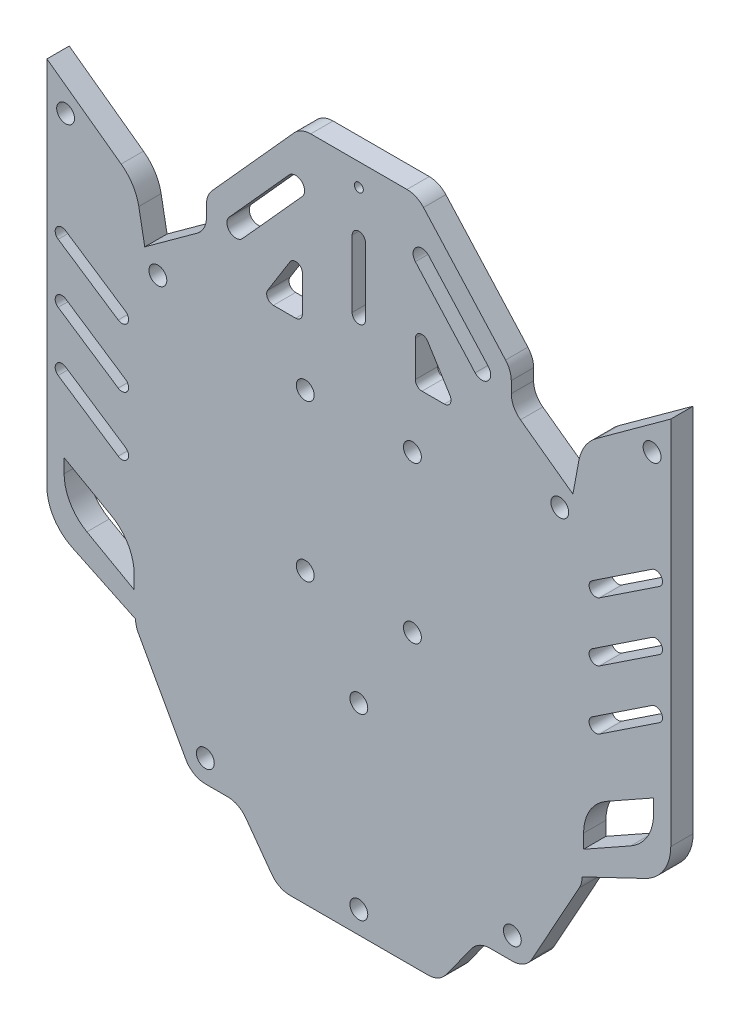
SolidWorks part; units mm, degrees
material "Acrylic (Medium-high impact)"
ref_plane "Front Plane" through (0, 0, 0) normal (0, 0, 1) x (1, 0, 0)
ref_plane "Top Plane" through (0, 0, 0) normal (0, 1, 0) x (1, 0, 0)
ref_plane "Right Plane" through (0, 0, 0) normal (1, 0, 0) x (0, 0, -1)
sketch "Sketch2" plane through (0, 0, 0) normal (0, 0, 1) x (1, 0, 0)
  line L0 (0, 0) -> (0, -150) construction
  line L1 (10.7739, 0) -> (-10.7739, 0)
  line L2 (-14.4896, -1.6543) -> (-32.8523, -22.0482)
  line L3 (-34.1366, -25.3939) -> (-34.1366, -27.9269)
  line L4 (-36.1977, -31.972) -> (-47.9389, -40.5025)
  line L6 (-19.4975, -147.9389) -> (-25.3193, -139.9258)
  line L7 (-29.3644, -137.8647) -> (-34.3726, -137.8647)
  line L8 (-38.7449, -135.2901) -> (-49.3724, -116.1315)
  line L9 (-15.4524, -150) -> (15.4524, -150)
  line L10 (19.4975, -147.9389) -> (25.3193, -139.9258)
  line L11 (29.3644, -137.8647) -> (34.3726, -137.8647)
  line L12 (38.7449, -135.2901) -> (49.3724, -116.1315)
  line L14 (36.1977, -31.972) -> (47.9389, -40.5025)
  line L15 (34.1366, -25.3939) -> (34.1366, -27.9269)
  line L16 (14.4896, -1.6543) -> (32.8523, -22.0482)
  line L17 (-14.147, -11.7352) -> (-27.5296, -26.5981) construction
  line L18 (-12.6607, -13.0735) -> (-26.0433, -27.9364)
  line L19 (-15.6333, -10.397) -> (-29.0159, -25.2599)
  line L20 (14.147, -37.4364) -> (19.147, -37.4364)
  line L21 (-14.147, -37.4364) -> (-19.147, -37.4364)
  line L22 (-12.647, -27.9364) -> (-12.647, -35.9364)
  line L24 (20.419, -35.1414) -> (15.419, -27.1414)
  line L26 (-20.419, -35.1414) -> (-15.419, -27.1414)
  line L27 (12.647, -27.9364) -> (12.647, -35.9364)
  line L28 (14.147, -11.7352) -> (27.5296, -26.5981) construction
  line L29 (12.6607, -13.0735) -> (26.0433, -27.9364)
  line L30 (15.6333, -10.397) -> (29.0159, -25.2599)
  line L31 (0, -15) -> (0, -30) construction
  line L32 (1.5, -15) -> (1.5, -30)
  line L33 (-1.5, -15) -> (-1.5, -30)
  line L34 (0, -50.308) -> (-12, -50.308) construction
  line L35 (14.147, -123.5201) -> (-14.147, -123.5201) construction
  line L36 (-50, -113.7061) -> (-64.1616, -106.9352)
  line L37 (-69.8481, -97.9134) -> (-69.8481, -15)
  line L38 (-69.8481, -15) -> (-53.2247, -27.0776)
  line L39 (-49.2712, -33.3393) -> (-47.9389, -40.5025)
  line L40 (-66.495, -47.4704) -> (-53.0582, -56.398) construction
  line L41 (-65.6648, -46.221) -> (-52.2281, -55.1487)
  line L42 (-67.3251, -48.7198) -> (-53.8883, -57.6474)
  line L43 (-66.495, -60.6771) -> (-53.0582, -69.6047) construction
  line L44 (-65.6648, -59.4277) -> (-52.2281, -68.3553)
  line L45 (-67.3251, -61.9264) -> (-53.8883, -70.8541)
  line L46 (-66.495, -73.8837) -> (-53.0582, -82.8114) construction
  line L47 (-65.6648, -72.6343) -> (-52.2281, -81.562)
  line L48 (-67.3251, -75.1331) -> (-53.8883, -84.0607)
  line L49 (-50.3296, -108.1791) -> (-60.8932, -102.2433)
  line L50 (-65.9945, -93.5254) -> (-65.9945, -90.4053)
  line L51 (-65.9945, -90.4053) -> (-55.4309, -96.3411)
  line L52 (-50.3296, -105.059) -> (-50.3296, -108.1791)
  line L53 (66.495, -47.4704) -> (53.0582, -56.398) construction
  line L54 (65.6648, -46.221) -> (52.2281, -55.1487)
  line L55 (67.3251, -48.7198) -> (53.8883, -57.6474)
  line L56 (66.495, -60.6771) -> (53.0582, -69.6047) construction
  line L57 (65.6648, -59.4277) -> (52.2281, -68.3553)
  line L58 (67.3251, -61.9264) -> (53.8883, -70.8541)
  line L59 (66.495, -73.8837) -> (53.0582, -82.8114) construction
  line L60 (65.6648, -72.6343) -> (52.2281, -81.562)
  line L61 (67.3251, -75.1331) -> (53.8883, -84.0607)
  line L62 (65.9945, -90.4053) -> (55.4309, -96.3411)
  line L63 (65.9945, -93.5254) -> (65.9945, -90.4053)
  line L64 (50.3296, -108.1791) -> (60.8932, -102.2433)
  line L65 (50.3296, -105.059) -> (50.3296, -108.1791)
  line L66 (50, -113.7061) -> (64.1616, -106.9352)
  line L67 (69.8481, -97.9134) -> (69.8481, -15)
  line L68 (69.8481, -15) -> (53.2247, -27.0776)
  line L69 (49.2712, -33.3393) -> (47.9389, -40.5025)
  arc A0 (-50, -113.7061) -> (-49.3724, -116.1315) centre (-45, -113.7061) ccw
  arc A1 (-19.4975, -147.9389) -> (-15.4524, -150) centre (-15.4524, -145) ccw
  arc A2 (-25.3193, -139.9258) -> (-29.3644, -137.8647) centre (-29.3644, -142.8647) ccw
  arc A3 (-34.3726, -137.8647) -> (-38.7449, -135.2901) centre (-34.3726, -132.8647) cw
  arc A5 (-34.1366, -27.9269) -> (-36.1977, -31.972) centre (-39.1366, -27.9269) cw
  arc A6 (-32.8523, -22.0482) -> (-34.1366, -25.3939) centre (-29.1366, -25.3939) ccw
  arc A7 (-10.7739, 0) -> (-14.4896, -1.6543) centre (-10.7739, -5) ccw
  arc A8 (19.4975, -147.9389) -> (15.4524, -150) centre (15.4524, -145) cw
  arc A9 (25.3193, -139.9258) -> (29.3644, -137.8647) centre (29.3644, -142.8647) cw
  arc A10 (34.3726, -137.8647) -> (38.7449, -135.2901) centre (34.3726, -132.8647) ccw
  arc A11 (50, -113.7061) -> (49.3724, -116.1315) centre (45, -113.7061) cw
  arc A13 (34.1366, -27.9269) -> (36.1977, -31.972) centre (39.1366, -27.9269) ccw
  arc A14 (32.8523, -22.0482) -> (34.1366, -25.3939) centre (29.1366, -25.3939) cw
  arc A15 (10.7739, 0) -> (14.4896, -1.6543) centre (10.7739, -5) cw
  arc A16 (-12.6607, -13.0735) -> (-15.6333, -10.397) centre (-14.147, -11.7352) ccw
  arc A17 (-29.0159, -25.2599) -> (-26.0433, -27.9364) centre (-27.5296, -26.5981) ccw
  circle A18 centre (0, -5) radius 1
  arc A19 (-12.647, -27.9364) -> (-15.419, -27.1414) centre (-14.147, -27.9364) ccw
  arc A20 (-14.147, -37.4364) -> (-12.647, -35.9364) centre (-14.147, -35.9364) ccw
  arc A21 (-14.147, -37.4364) -> (-12.647, -35.9364) centre (-14.147, -35.9364) ccw
  arc A22 (-20.419, -35.1414) -> (-19.147, -37.4364) centre (-19.147, -35.9364) ccw
  arc A23 (20.419, -35.1414) -> (19.147, -37.4364) centre (19.147, -35.9364) cw
  arc A24 (12.647, -27.9364) -> (15.419, -27.1414) centre (14.147, -27.9364) cw
  arc A25 (14.147, -37.4364) -> (12.647, -35.9364) centre (14.147, -35.9364) cw
  arc A26 (12.6607, -13.0735) -> (15.6333, -10.397) centre (14.147, -11.7352) cw
  arc A27 (29.0159, -25.2599) -> (26.0433, -27.9364) centre (27.5296, -26.5981) cw
  arc A28 (1.5, -15) -> (-1.5, -15) centre (0, -15) ccw
  arc A29 (-1.5, -30) -> (1.5, -30) centre (0, -30) ccw
  circle A30 centre (0, -145) radius 2
  circle A31 centre (0, -105) radius 2
  circle A32 centre (-12, -50.308) radius 2
  circle A33 centre (12, -50.308) radius 2
  circle A34 centre (12, -85.308) radius 2
  circle A35 centre (-12, -85.308) radius 2
  circle A36 centre (-34.3726, -132.8647) radius 2
  circle A37 centre (34.3726, -132.8647) radius 2
  circle A38 centre (-45, -44.5476) radius 2
  circle A39 centre (45, -44.5476) radius 2
  arc A40 (-65.6648, -46.221) -> (-67.3251, -48.7198) centre (-66.495, -47.4704) ccw
  arc A41 (-53.8883, -57.6474) -> (-52.2281, -55.1487) centre (-53.0582, -56.398) ccw
  arc A42 (-65.6648, -59.4277) -> (-67.3251, -61.9264) centre (-66.495, -60.6771) ccw
  arc A43 (-53.8883, -70.8541) -> (-52.2281, -68.3553) centre (-53.0582, -69.6047) ccw
  arc A44 (-65.6648, -72.6343) -> (-67.3251, -75.1331) centre (-66.495, -73.8837) ccw
  arc A45 (-53.8883, -84.0607) -> (-52.2281, -81.562) centre (-53.0582, -82.8114) ccw
  circle A46 centre (-65.6648, -23.4746) radius 2
  arc A47 (-60.8932, -102.2433) -> (-65.9945, -93.5254) centre (-55.9945, -93.5254) cw
  arc A48 (-64.1616, -106.9352) -> (-69.8481, -97.9134) centre (-59.8481, -97.9134) cw
  arc A49 (-55.4309, -96.3411) -> (-50.3296, -105.059) centre (-60.3296, -105.059) cw
  circle A50 centre (65.6648, -23.4746) radius 2
  arc A51 (65.6648, -46.221) -> (67.3251, -48.7198) centre (66.495, -47.4704) cw
  arc A52 (53.8883, -57.6474) -> (52.2281, -55.1487) centre (53.0582, -56.398) cw
  arc A53 (65.6648, -59.4277) -> (67.3251, -61.9264) centre (66.495, -60.6771) cw
  arc A54 (53.8883, -70.8541) -> (52.2281, -68.3553) centre (53.0582, -69.6047) cw
  arc A55 (65.6648, -72.6343) -> (67.3251, -75.1331) centre (66.495, -73.8837) cw
  arc A56 (53.8883, -84.0607) -> (52.2281, -81.562) centre (53.0582, -82.8114) cw
  arc A57 (60.8932, -102.2433) -> (65.9945, -93.5254) centre (55.9945, -93.5254) ccw
  arc A58 (55.4309, -96.3411) -> (50.3296, -105.059) centre (60.3296, -105.059) ccw
  arc A59 (64.1616, -106.9352) -> (69.8481, -97.9134) centre (59.8481, -97.9134) ccw
  arc A60 (53.2247, -27.0776) -> (49.2712, -33.3393) centre (59.1026, -35.1677) ccw
  arc A61 (-53.2247, -27.0776) -> (-49.2712, -33.3393) centre (-59.1026, -35.1677) cw
  text T0 "OCOBOT" font "Exotc350 Bd BT" height 4
  point P13 (-50, -115)
  point P16 (-18, -150)
  point P19 (-26.8168, -137.8647)
  point P22 (-37.3168, -137.8647)
  point P25 (-50, -42)
  point P28 (-34.1366, -30.4746)
  point P31 (-34.1366, -23.4746)
  point P34 (-13, 0)
  point P56 (34.1366, -23.4746)
  point P62 (-20.8383, -19.1667)
  point P71 (-18.0805, -35.9364)
  point P73 (-14.147, -31.9364)
  point P76 (0, -22.5)
  point P100 (20.8383, -19.1667)
  point P111 (0, -75)
  point P125 (0, -123.5201)
  point P129 (-59.7766, -51.9342)
  point P136 (-59.7766, -65.1409)
  point P143 (-59.7766, -78.3475)
  point P164 (59.7766, -51.9342)
  point P171 (59.7766, -65.1409)
  point P178 (59.7766, -78.3475)
  point P198 (50, -29.4205)
  point P201 (-50, -29.4205)
  dimension "D10" = 5
  dimension "D13" = 8
  dimension "D14" = 5
  dimension "D16" = 2
  dimension "D19" = 2
  dimension "D20" = 5
  dimension "D24" = 1.5
  dimension "D25" = 1.5
  dimension "D26" = 1.5
  dimension "D34" = 1.5
  dimension "D37" = 4
  dimension "D38" = 4
  dimension "D40" = 4
  dimension "D47" = 4
  dimension "D48" = 4
  dimension "D49" = 5
  dimension "D50" = 4
  dimension "D51" = 4
  dimension "D52" = 4
  dimension "D53" = 4
  dimension "D54" = 1.5
  dimension "D55" = 1.5
  dimension "D58" = 4
  dimension "D57" = 1.5
  dimension "D59" = 10
  dimension "D60" = 10
  dimension "D61" = 10
  dimension "D64" = 16.1322
  dimension "D70" = 20.3724
  dimension "D72" = 64.536
  dimension "D73" = 13.425
  dimension "D1" = 150
  dimension "D2" = 100
  dimension "D3" = 73
  dimension "D4" = 36
  dimension "D5" = 15
  dimension "D6" = 26
  dimension "D7" = 35
  dimension "D8" = 10.5
  dimension "D9" = 54
  dimension "D11" = 48
  dimension "D12" = 7
  dimension "D15" = 5
  dimension "D17" = 14.147
  dimension "D18" = 20
  dimension "D21" = 8
  dimension "D22" = 5
  dimension "D23" = 14.147
  dimension "D27" = 19.478
  dimension "D28" = 112.5636
  dimension "D29" = 31.9364
  dimension "D30" = 27.9364
  dimension "D31" = 14.147
  dimension "D32" = 18.0805
  dimension "D33" = 35.9364
  dimension "D35" = 15
  dimension "D36" = 15
  dimension "D39" = 40
  dimension "D41" = 12
  dimension "D42" = 50.308
  dimension "D43" = 35
  dimension "D44" = 24
  dimension "D45" = 35
  dimension "D46" = 35
  dimension "D56" = 8
  dimension "D62" = 4.269
  dimension "D63" = 82.9134
  dimension "D65" = 24.1586
  dimension "D66" = 144.571
  dimension "D67" = 53.0582
  dimension "D68" = 54.3957
  dimension "D69" = 21.9088
  dimension "D71" = 2.5331
  dimension "D74" = 4.1832
  dimension "D75" = 8.4746
  dimension "D76" = 5
  dimension "D77" = 45
  dimension "D78" = 3.3531
  dimension "D79" = 32.4704
  dimension "D80" = 5.5368
  dimension "D81" = 12.1171
  dimension "D82" = 75.4053
  dimension "D83" = 100.6593
  dimension "D84" = 97.9389
  dimension "D85" = 26.4799
extrude "Boss-Extrude2" add sketch "Sketch2" along normal blind 5 contours A61 L38 L37 A48 L36 A0 L8 A3 L7 A2 L6 A1 L9 A8 L10 A9 L11 A10 L12 A11 L66 A59 L67 L68 A60 L69 L14 A13 L15 A14 L16 A15 L1 A7 L2 A6 L3 A5 L4 L39 A58 L62 L63 A57 L64 L65 L51 A49 L52
